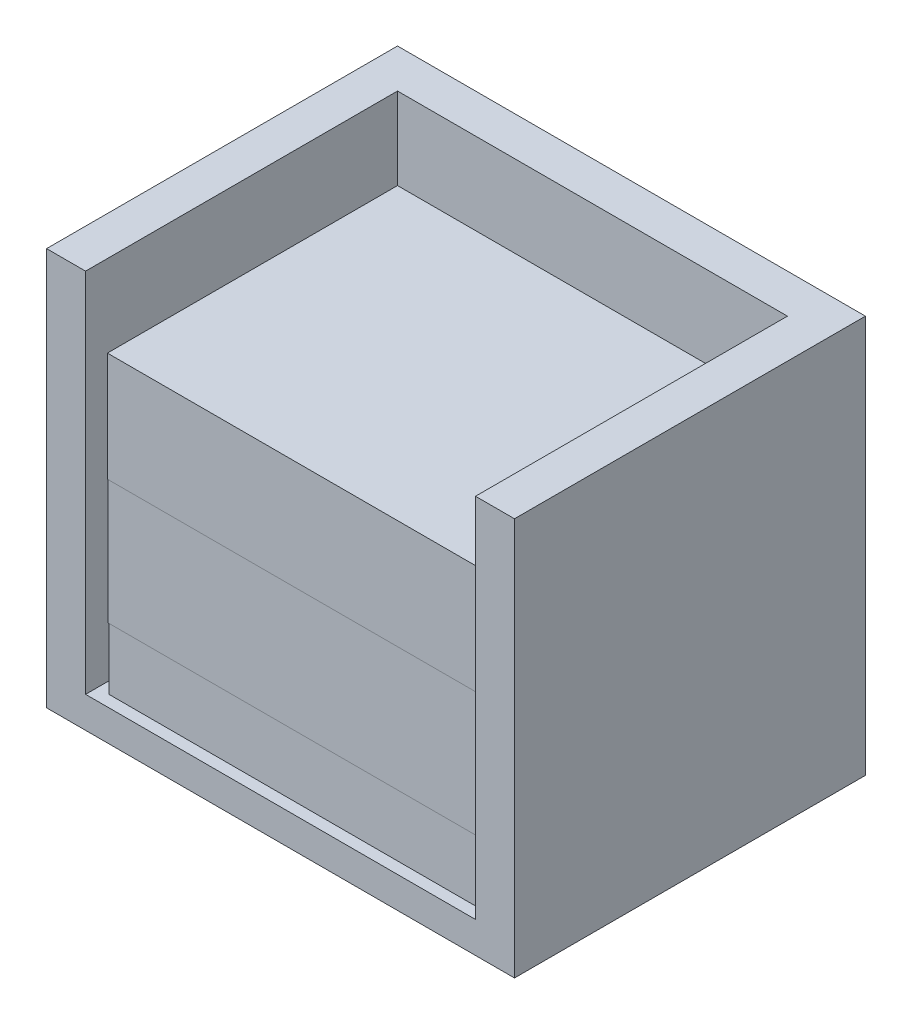
SolidWorks part; units mm, degrees
ref_plane "Front Plane" through (0, 0, 0) normal (0, 0, 1) x (1, 0, 0)
ref_plane "Top Plane" through (0, 0, 0) normal (0, 1, 0) x (1, 0, 0)
ref_plane "Right Plane" through (0, 0, 0) normal (1, 0, 0) x (0, 0, -1)
sketch "Sketch1" plane through (0, 0, 0) normal (0, 1, 0) x (1, 0, 0)
  line L1 (-298.4772, 234.5178) -> (301.5228, 234.5178)
  line L2 (-298.4772, 234.5178) -> (-298.4772, -215.4822)
  line L3 (-298.4772, -215.4822) -> (301.5228, -215.4822)
  line L4 (301.5228, 234.5178) -> (301.5228, -215.4822)
  line L5 (-298.4772, 234.5178) -> (-248.4772, 234.5178)
  line L6 (-298.4772, 234.5178) -> (-298.4772, -215.4822)
  line L7 (-298.4772, -215.4822) -> (-248.4772, -215.4822)
  line L8 (-248.4772, 184.5178) -> (-248.4772, -215.4822)
  line L9 (301.5228, 234.5178) -> (251.5228, 234.5178)
  line L10 (301.5228, 234.5178) -> (301.5228, -215.4822)
  line L11 (301.5228, -215.4822) -> (251.5228, -215.4822)
  line L12 (251.5228, 184.5178) -> (251.5228, -215.4822)
  line L13 (-298.4772, 234.5178) -> (301.5228, 234.5178)
  line L14 (-298.4772, 234.5178) -> (-298.4772, 184.5178)
  line L15 (-248.4772, 184.5178) -> (251.5228, 184.5178)
  line L16 (301.5228, 234.5178) -> (301.5228, 184.5178)
  dimension "D1" = 600
  dimension "D2" = 450
  dimension "D3" = 50
  dimension "D4" = 50
  dimension "D5" = 50
extrude "Boss-Extrude2" add sketch "Sketch1" along normal blind 510 contours L8 L15 L12 L3 L10 L4 L1 L2 L6 | L15 L8 L3 L12
sketch "Sketch2" plane through (0, 510, 0) normal (0, 1, 0) x (1, 0, 0)
  line L0 (-298.4772, -215.4822) -> (301.5228, -215.4822) construction
  line L1 (-298.4772, 234.5178) -> (-248.4772, 234.5178)
  line L2 (-298.4772, 234.5178) -> (-298.4772, -215.4822)
  line L3 (-298.4772, -215.4822) -> (-248.4772, -215.4822)
  line L4 (-248.4772, 184.5178) -> (-248.4772, -215.4822)
  line L5 (-248.4772, -215.4822) -> (251.5228, -215.4822)
  line L6 (301.5228, 234.5178) -> (251.5228, 234.5178)
  line L7 (301.5228, 234.5178) -> (301.5228, -215.4822)
  line L8 (301.5228, -215.4822) -> (251.5228, -215.4822)
  line L9 (251.5228, 184.5178) -> (251.5228, -215.4822)
  line L10 (-298.4772, 234.5178) -> (301.5228, 234.5178)
  line L11 (-298.4772, 234.5178) -> (-298.4772, 184.5178)
  line L12 (-248.4772, 184.5178) -> (251.5228, 184.5178)
  line L13 (301.5228, 234.5178) -> (301.5228, 184.5178)
  line M2 (-298.4772, -215.4822) -> (301.5228, -215.4822)
  dimension "D1" = 50
  dimension "D2" = 50
  dimension "D3" = 50
extrude "Cut-Extrude1" cut sketch "Sketch2" against normal blind 470 contours L12 L4 L9 M2
sketch "Sketch3" plane through (0, 40, 0) normal (0, 1, 0) x (1, 0, 0)
  line L1 (-248.4772, 184.5178) -> (251.5228, 184.5178)
  line L2 (-248.4772, 184.5178) -> (-248.4772, -215.4822)
  line L3 (-248.4772, -215.4822) -> (251.5228, -215.4822)
  line L4 (251.5228, 184.5178) -> (251.5228, -215.4822)
sketch "Sketch4" plane through (0, 40, 0) normal (0, 1, 0) x (1, 0, 0)
  line L0 (-248.4772, -215.4822) -> (251.5228, -215.4822) construction
  line L1 (236.5228, -215.4822) -> (-233.4772, -215.4822)
  line L2 (236.5228, -215.4822) -> (236.5228, 169.5178)
  line L3 (236.5228, 169.5178) -> (-233.4772, 169.5178)
  line L4 (-233.4772, -215.4822) -> (-233.4772, 169.5178)
  line L6 (-248.4772, 184.5178) -> (251.5228, 184.5178)
  line L7 (-248.4772, 184.5178) -> (-248.4772, -215.4822)
  line L8 (-248.4772, -215.4822) -> (251.5228, -215.4822)
  line L9 (251.5228, 184.5178) -> (251.5228, -215.4822)
  line L10 (-233.4772, -215.4822) -> (236.5228, -215.4822)
  line L11 (-233.4772, -215.4822) -> (-233.4772, -200.4822)
  line L12 (-233.4772, -200.4822) -> (236.5228, -200.4822)
  line L13 (236.5228, -215.4822) -> (236.5228, -200.4822)
  dimension "D1" = 15
  dimension "D2" = 15
  dimension "D3" = 15
  dimension "D4" = 15
extrude "Boss-Extrude5" add sketch "Sketch4" along normal blind 80 contours L4 L12 L2 L3
sketch "Sketch5" plane through (0, 120, 0) normal (0, 1, 0) x (1, 0, 0)
  line L1 (-233.4772, 169.5178) -> (236.5228, 169.5178)
  line L2 (-233.4772, 169.5178) -> (-233.4772, -200.4822)
  line L3 (-233.4772, -200.4822) -> (236.5228, -200.4822)
  line L4 (236.5228, 169.5178) -> (236.5228, -200.4822)
sketch "Sketch6" plane through (0, 120, 0) normal (0, 1, 0) x (1, 0, 0)
  line L1 (-233.4772, 169.5178) -> (237.4821, 169.5178)
  line L2 (-233.4772, 169.5178) -> (-233.4772, -201.6713)
  line L3 (-233.4772, -201.6713) -> (237.4821, -201.6713)
  line L4 (237.4821, 169.5178) -> (237.4821, -201.6713)
extrude "Boss-Extrude7" add sketch "Sketch6" along normal blind 160
sketch "Sketch7" plane through (0, 280, 0) normal (0, 1, 0) x (1, 0, 0)
  line L1 (-233.4772, 169.5178) -> (239.1761, 169.5178)
  line L2 (-233.4772, 169.5178) -> (-233.4772, -202.5218)
  line L3 (-233.4772, -202.5218) -> (239.1761, -202.5218)
  line L4 (239.1761, 169.5178) -> (239.1761, -202.5218)
extrude "Boss-Extrude8" add sketch "Sketch7" along normal blind 140
sketch "Sketch8" plane through (0, 0, 0) normal (0, -1, 0) x (1, 0, 0)
  circle A0 centre (0, 0) radius 150
  dimension "D1" = 300
extrude "Cut-Extrude2" cut sketch "Sketch8" against normal blind 90
